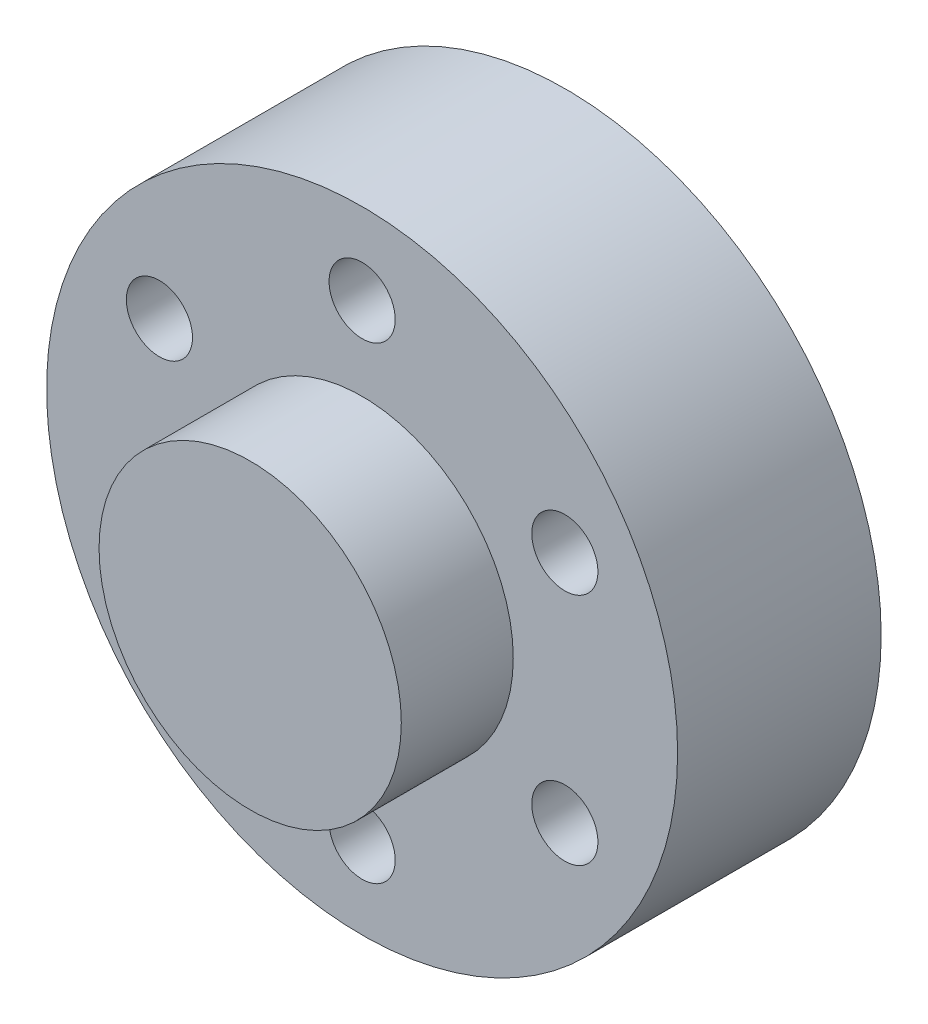
SolidWorks part; units mm, degrees
ref_plane "Front Plane" through (0, 0, 0) normal (0, 0, 1) x (1, 0, 0)
ref_plane "Top Plane" through (0, 0, 0) normal (0, 1, 0) x (1, 0, 0)
ref_plane "Right Plane" through (0, 0, 0) normal (1, 0, 0) x (0, 0, -1)
sketch "Sketch2" plane through (0, 0, 0) normal (0, 0, 1) x (1, 0, 0)
  line L0 (0, 20.3178) -> (0, -21.083) construction
  circle A0 centre (0, 0) radius 9.5
  circle A1 centre (0, 0) radius 11.5 construction
  circle A3 centre (0, 0) radius 15.5
  circle A4 centre (0, 11.5) radius 1.625
  circle A10 centre (9.9593, 5.75) radius 1.625
  circle A11 centre (9.9593, -5.75) radius 1.625
  circle A12 centre (0, -11.5) radius 1.625
  circle A13 centre (-9.9593, -5.75) radius 1.625
  circle A14 centre (-9.9593, 5.75) radius 1.625
  point P21 (1.7321, -1)
  point P22 (0.866, -0.5)
  point P23 (0, 0)
  dimension "D1" = 19
  dimension "D2" = 6
  dimension "D3" = 23
  dimension "D4" = 31
  dimension "D5" = 3.25
extrude "Boss-Extrude1" add sketch "Sketch2" along normal blind 10
sketch "Sketch3" plane through (0, 0, 10) normal (0, 0, 1) x (1, 0, 0)
  circle A0 centre (0, 0) radius 7.425
  dimension "D1" = 14.85
extrude "Boss-Extrude2" add sketch "Sketch3" along normal blind 5.5
sketch "Sketch6" plane through (0, 0, 0) normal (0, 0, -1) x (-1, 0, 0)
  circle A0 centre (0, 0) radius 7.425
  dimension "D1" = 14.85
extrude "Boss-Extrude4" add sketch "Sketch6" along normal blind 5.5 contours A0
sketch "Sketch7" plane through (0, 0, -5.5) normal (0, 0, -1) x (-1, 0, 0)
  circle A0 centre (0, 0) radius 2
  dimension "D1" = 4
extrude "Boss-Extrude5" add sketch "Sketch7" along normal blind 1
fillet "Fillet2" radius 0.05 1 edges at (-2, 0, -6.5)
sketch "Sketch9" plane through (0, 0, -6.5) normal (0, 0, -1) x (-1, 0, 0)
  line L1 (-1.2247, 1.25) -> (1.2247, 1.25)
  arc A0 (-1.2247, 1.25) -> (1.2247, 1.25) centre (0, 0) ccw
  circle A1 centre (0, -0.25) radius 1.5 construction
  dimension "D1" = 3.5
  dimension "D2" = 3
extrude "Cut-Extrude1" cut sketch "Sketch9" against normal blind 11
